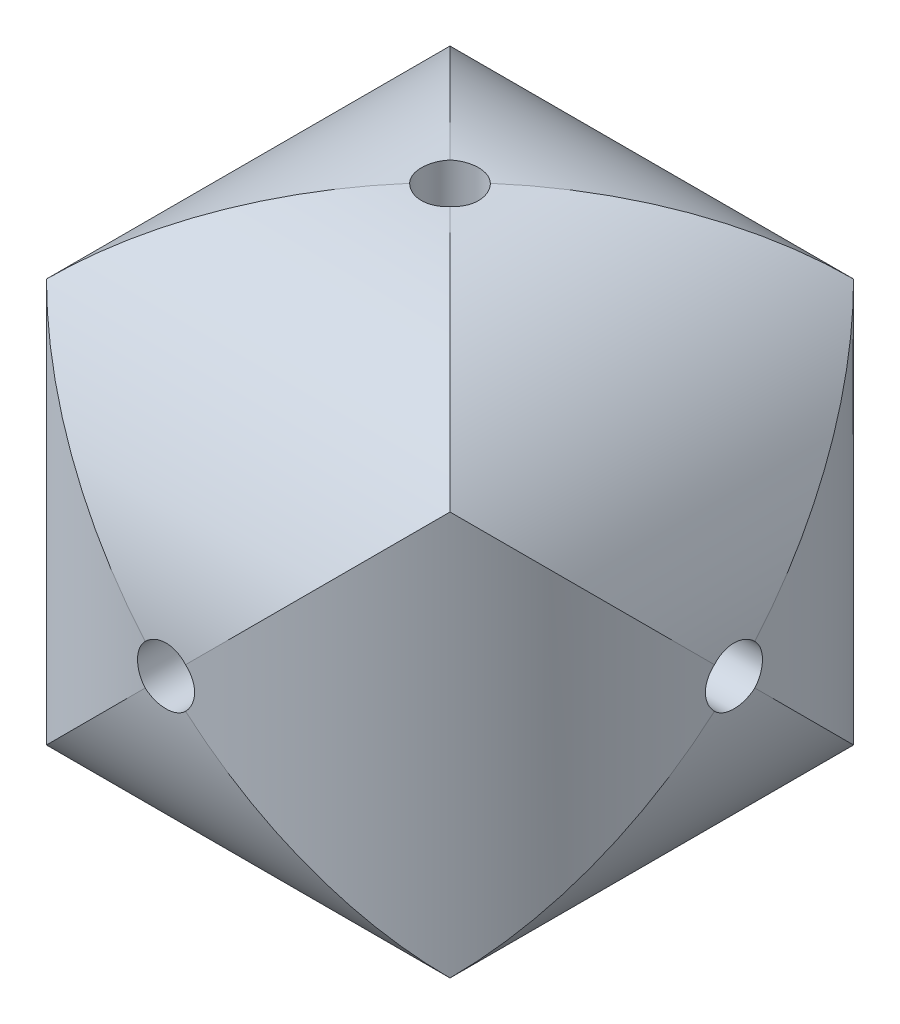
SolidWorks part; units mm, degrees
ref_plane "前视基准面" through (0, 0, 0) normal (0, 0, 1) x (1, 0, 0)
ref_plane "上视基准面" through (0, 0, 0) normal (0, 1, 0) x (1, 0, 0)
ref_plane "右视基准面" through (0, 0, 0) normal (1, 0, 0) x (0, 0, -1)
other "Configuration Table"
sketch "草图2" plane through (0, 0, 0) normal (0, 1, 0) x (1, 0, 0)
  line L1 (-10, 10) -> (10, 10)
  line L2 (-10, 10) -> (-10, -10)
  line L3 (-10, -10) -> (10, -10)
  line L4 (10, 10) -> (10, -10)
  line L5 (-10, 10) -> (10, -10) construction
  line L6 (-10, -10) -> (10, 10) construction
  point P0 (0, 0)
  dimension "D1" = 20
extrude "凸台-拉伸1" add sketch "草图2" along normal mid plane 20
sketch "草图3" plane through (0, 0, 10) normal (0, 0, 1) x (1, 0, 0)
  circle A0 centre (0, 0) radius 5
  dimension "D1" = 10
extrude "切除-拉伸1" cut sketch "草图3" against normal blind 20 flip side to cut
sketch "草图4" plane through (0, 0, 0) normal (0, 1, 0) x (1, 0, 0)
  circle A0 centre (0, 0) radius 5
  dimension "D1" = 10
extrude "切除-拉伸2" cut sketch "草图4" against normal mid plane 20 flip side to cut
sketch "草图5" plane through (0, 0, 0) normal (1, 0, 0) x (0, 0, -1)
  circle A0 centre (0, 0) radius 5
  dimension "D1" = 10
extrude "切除-拉伸3" cut sketch "草图5" against normal mid plane 20 flip side to cut
sketch "草图6" plane through (0, 0, 0) normal (1, 0, 0) x (0, 0, -1)
  circle A0 centre (0, 0) radius 0.5
  dimension "D1" = 1
extrude "切除-拉伸4" cut sketch "草图6" against normal up to next
ref_axis "基准轴1" through (0, 5.5, 0) along (0, -1, 0)
pattern_circular "阵列(圆周)1" count 4 over 360 about axis through (0, 5.5, 0) along (0, -1, 0) of "切除-拉伸4"
sketch "草图7" plane through (0, 0, 0) normal (0, 1, 0) x (1, 0, 0)
  circle A0 centre (0, 0) radius 0.5
  dimension "D1" = 1
extrude "切除-拉伸5" cut sketch "草图7" against normal through all both and the other way through all
